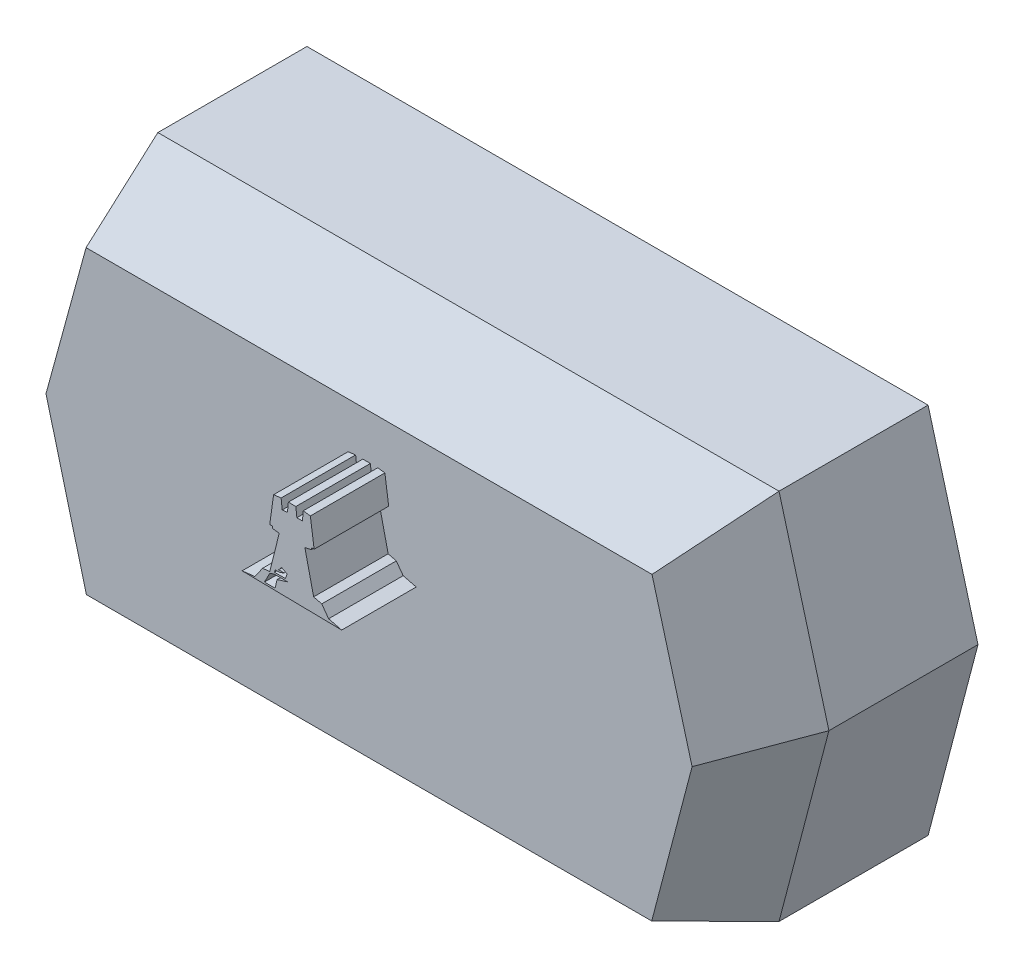
SolidWorks part; units mm, degrees
ref_plane "前视基准面" through (0, 0, 0) normal (0, 0, 1) x (1, 0, 0)
ref_plane "上视基准面" through (0, 0, 0) normal (0, 1, 0) x (1, 0, 0)
ref_plane "右视基准面" through (0, 0, 0) normal (1, 0, 0) x (0, 0, -1)
sketch "草图1" plane through (0, 0, 0) normal (0, 0, 1) x (1, 0, 0)
  line L0 (-12.5, 7.5) -> (-14.5088, 0.1562)
  line L1 (-12.5, -7.5) -> (12.5, -7.5)
  line L3 (-12.5, 7.5) -> (12.5, 7.5)
  line L5 (-12.5, -7.5) -> (12.5, 7.5) construction
  line L6 (-12.5, 7.5) -> (12.5, -7.5) construction
  line L7 (-14.5088, 0.1562) -> (-12.5, -7.5)
  line L8 (0, 0) -> (0, 4.8026) construction
  line L9 (14.5088, 0.1562) -> (12.5, -7.5)
  line L10 (12.5, 7.5) -> (14.5088, 0.1562)
  point P0 (0, 0)
extrude "凸台-拉伸1" add sketch "草图1" along normal blind 10
chamfer "倒角4" distance 4 angle 20 6 edges at (13.5044, -3.6719, 10) (0, -7.5, 10) (-13.5044, -3.6719, 10) (-13.5044, 3.8281, 10) (0, 7.5, 10) (13.5044, 3.8281, 10)
sketch "草图4" plane through (0, 0, 10) normal (0, 0, 1) x (1, 0, 0)
  line L0 (192.915, 588.9204) -> (980.2483, 588.9204) construction
  line L1 (-0.8423, 4.2049) -> (-0.9971, 3.0827)
  line L2 (-0.9971, 3.0827) -> (-0.8754, 3.0961)
  line L3 (-0.8754, 3.0961) -> (-0.8834, 3.0104)
  line L4 (-0.8834, 3.0104) -> (-0.615, 2.9739)
  line L5 (-0.615, 2.9739) -> (-0.9971, 1.4513)
  line L6 (-0.9971, 1.4513) -> (-1.2865, 1.4195)
  line L7 (-1.2865, 1.4195) -> (-1.593, 0.9773)
  line L8 (-1.593, 0.9773) -> (-2.1073, 0.9209)
  line L9 (-2.1073, 0.9209) -> (1.8984, 0.8586)
  line L10 (1.8984, 0.8586) -> (1.3732, 0.9904)
  line L11 (1.3732, 0.9904) -> (1.0968, 1.3692)
  line L12 (1.0968, 1.3692) -> (0.7698, 1.4513)
  line L13 (0.7698, 1.4513) -> (0.4173, 2.9921)
  line L14 (0.4173, 2.9921) -> (0.6844, 3.0532)
  line L15 (0.6844, 3.0532) -> (0.6844, 3.1209)
  line L16 (0.6844, 3.1209) -> (0.7901, 3.1209)
  line L17 (0.7901, 3.1209) -> (0.6371, 4.2049)
  line L18 (0.6371, 4.2049) -> (0.3533, 4.2435)
  line L19 (0.3533, 4.2435) -> (0.3185, 3.8706)
  line L20 (0.3185, 3.8706) -> (0.0955, 3.8706)
  line L21 (0.0955, 3.8706) -> (0.0545, 4.2435)
  line L22 (0.0545, 4.2435) -> (-0.2486, 4.2435)
  line L23 (-0.2486, 4.2435) -> (-0.2834, 3.8706)
  line L24 (-0.2834, 3.8706) -> (-0.4961, 3.8472)
  line L25 (-0.4961, 3.8472) -> (-0.5396, 4.2435)
  line L26 (-0.5396, 4.2435) -> (-0.8423, 4.2049)
  line L27 (-1.2107, 0.9773) -> (-0.7839, 0.9773)
  line L28 (-0.7839, 0.9773) -> (-0.6975, 1.3216)
  line L29 (-0.6975, 1.3216) -> (-0.266, 1.4513)
  line L30 (-0.266, 1.4513) -> (-0.8061, 1.4513)
  line L31 (-0.8061, 1.4513) -> (-0.991, 1.3957)
  line L32 (-0.991, 1.3957) -> (-1.2107, 0.9773)
  line L33 (-0.8061, 1.5213) -> (-0.3648, 1.5213)
  line L34 (-0.3648, 1.5213) -> (-0.299, 1.7136)
  line L35 (-0.299, 1.7136) -> (-0.4335, 1.7842)
  line L36 (-0.4335, 1.7842) -> (-0.5179, 1.8285)
  line L37 (-0.5179, 1.8285) -> (-0.6356, 1.6933)
  line L38 (-0.6356, 1.6933) -> (-0.418, 1.6933)
  line L39 (-0.418, 1.6933) -> (-0.5854, 1.6174)
  line L40 (-0.5854, 1.6174) -> (-0.7746, 1.6174)
  line L41 (-0.7746, 1.6174) -> (-0.8061, 1.5213)
extrude "凸台-拉伸2" add sketch "草图4" along normal blind 3
